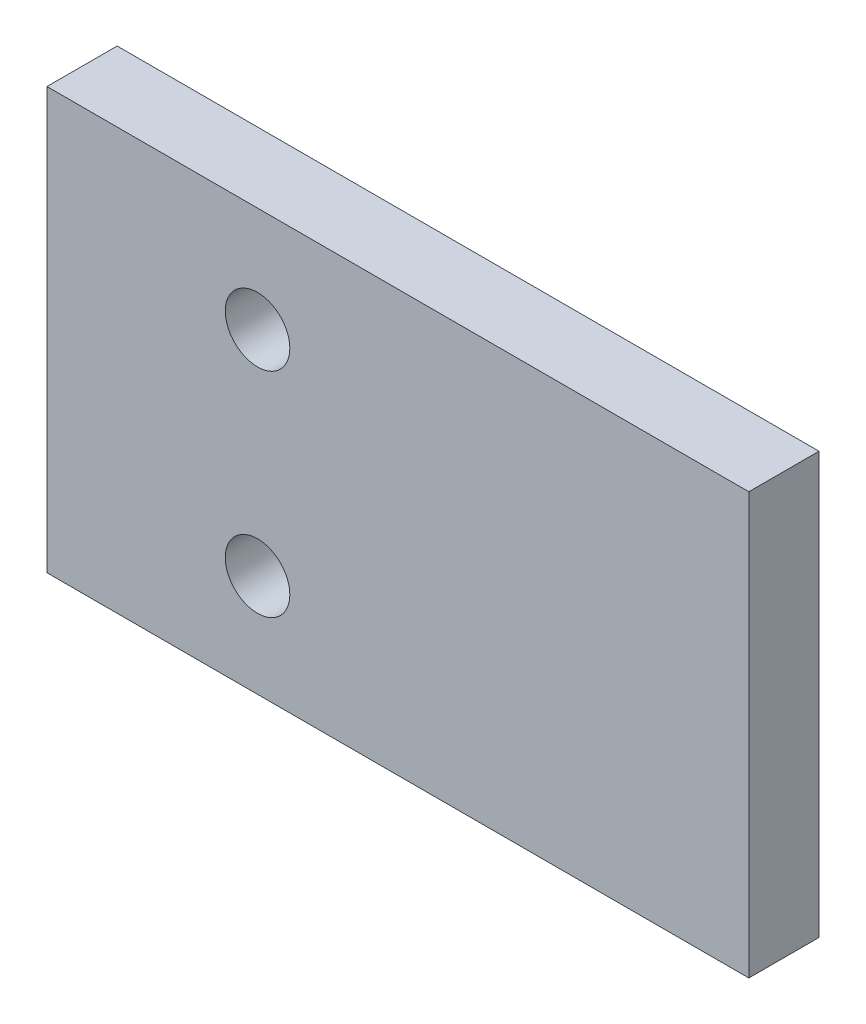
SolidWorks part; units mm, degrees
ref_plane "Front Plane" through (0, 0, 0) normal (0, 0, 1) x (1, 0, 0)
ref_plane "Top Plane" through (0, 0, 0) normal (0, 1, 0) x (1, 0, 0)
ref_plane "Right Plane" through (0, 0, 0) normal (1, 0, 0) x (0, 0, -1)
sketch "Sketch1" plane through (0, 0, 0) normal (0, 0, 1) x (1, 0, 0)
  line L1 (184.15, 19.05) -> (215.9, 19.05)
  line L2 (184.15, 19.05) -> (184.15, 0)
  line L3 (184.15, 0) -> (215.9, 0)
  line L4 (215.9, 19.05) -> (215.9, 0)
extrude "Boss-Extrude1" add sketch "Sketch1" along normal blind 3.175 contours L1 L4 L3 L2
sketch "Sketch2" plane through (0, 0, 3.175) normal (0, 0, 1) x (1, 0, 0)
  line L0 (184.15, 19.05) -> (193.675, 19.05) construction
  line L1 (184.15, 19.05) -> (215.9, 19.05) construction
  line L2 (193.675, 19.05) -> (193.675, 14.2875) construction
  line L3 (193.675, 14.2875) -> (193.675, 4.6355) construction
  circle A0 centre (193.675, 14.2875) radius 1.4605
  circle A1 centre (193.675, 4.6355) radius 1.4605
  dimension "D4" = 2.921
  dimension "D5" = 2.921
  dimension "D1" = 9.525
  dimension "D2" = 4.7625
  dimension "D3" = 9.652
extrude "Cut-Extrude1" cut sketch "Sketch2" against normal blind 9.525
